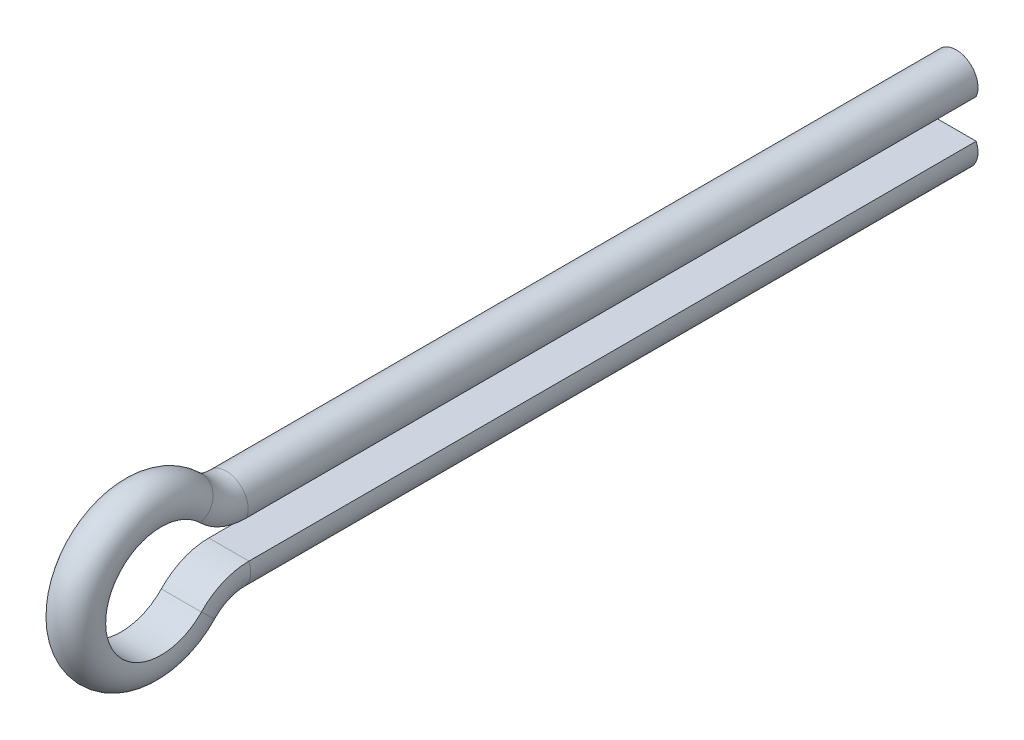
SolidWorks part; units mm, degrees
ref_plane "Front Plane" through (0, 0, 0) normal (0, 0, 1) x (1, 0, 0)
ref_plane "Top Plane" through (0, 0, 0) normal (0, 1, 0) x (1, 0, 0)
ref_plane "Right Plane" through (0, 0, 0) normal (1, 0, 0) x (0, 0, -1)
sketch "Sketch1" plane through (0, 0, 0) normal (1, 0, 0) x (0, 0, -1)
  line L0 (-39.5418, 0) -> (186.3338, 0) construction
  line L1 (-20.0832, 4.7143) -> (146.7697, 4.7143)
  line L2 (-19.4968, -4.1177) -> (146.7697, -4.1177)
  arc A0 (-30.6204, 9.0387) -> (-30.3515, -8.7652) centre (-39.5418, 0) ccw
  arc A1 (-19.4968, -4.1177) -> (-30.3515, -8.7652) centre (-19.4968, -19.1177) ccw
  arc A2 (-30.6204, 9.0387) -> (-20.0832, 4.7143) centre (-20.0832, 19.7143) ccw
  dimension "D1" = 25.4
  dimension "D2" = 15
ref_plane "Plane1" through (0, 4.7143, -146.7697) normal (0, 0, -1) x (-1, 0, 0)
sketch "Sketch2" plane through (0, 4.7143, -146.7697) normal (0, 0, -1) x (-1, 0, 0)
  line L0 (0, 7.9857) -> (0, -17.4143) construction
  line L1 (-4.5826, -0.0044) -> (4.5826, -0.0044)
  arc A0 (4.5826, -0.0044) -> (-4.5826, -0.0044) centre (0, 1.9956) ccw
  dimension "D1" = 10
  dimension "D2" = 2
sweep "Sweep1" add profiles "Sketch2" path "Sketch1"
